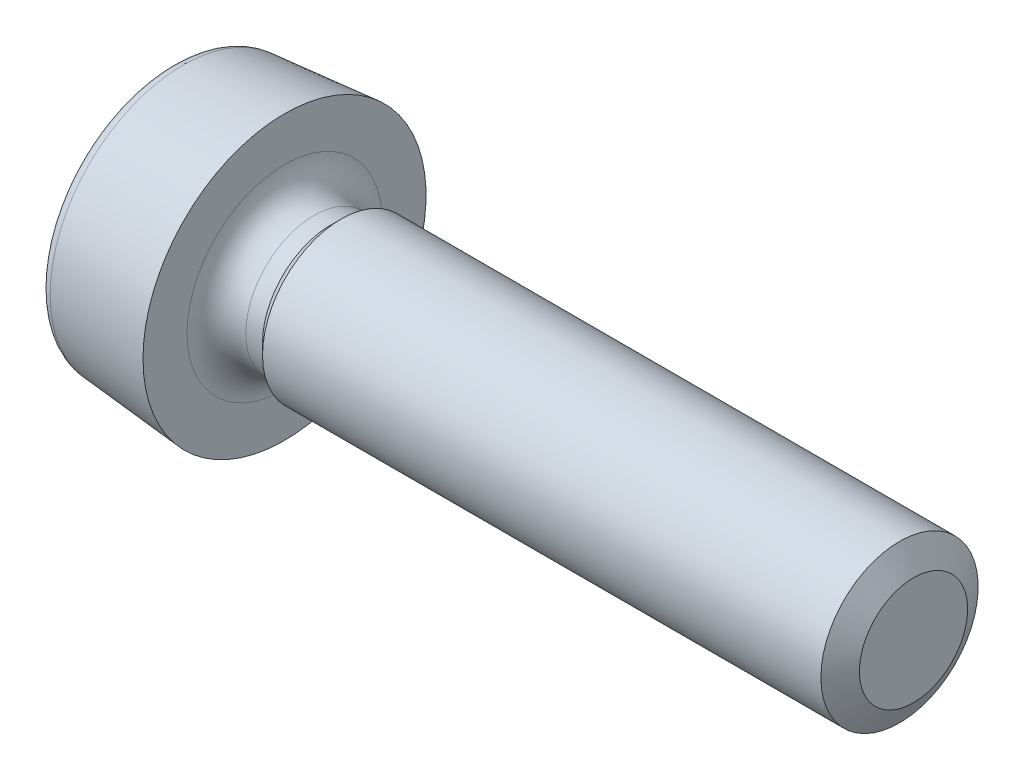
SolidWorks part; units mm, degrees
revolve "基体-旋转" add sketch "草图3" angle 360 about L0
sketch "草图3" plane through (0, 0, 0) normal (0, 0, 1) x (1, 0, 0)
  line L0 (-2.1696, 0) -> (16.014, 0) construction
  line L1 (0, 0) -> (11.8, 0)
  line L2 (11.8, 0) -> (11.8, 1.25)
  line L3 (11.8, 1.25) -> (2.7, 1.25)
  line L4 (2.7, 1.25) -> (2.5325, 1.0825)
  line L5 (2.5325, 1.0825) -> (2.2675, 1.0825)
  line L7 (1.8, 2.25) -> (0.1826, 2.1085)
  line L8 (0, 1.9093) -> (0, 0)
  line L9 (1.8, 1.55) -> (1.8, 2.25)
  arc A0 (1.8, 1.55) -> (2.2675, 1.0825) centre (2.2675, 1.55) ccw
  arc A1 (0.1826, 2.1085) -> (0, 1.9093) centre (0.2, 1.9093) ccw
  dimension "D4" = 0.2
  dimension "D1" = 5
  dimension "dk" = 4.5
  dimension "d" = 2.5
  dimension "D2" = 45
  dimension "da" = 3.1
  dimension "k" = 1.8
  dimension "D3" = 2.165
  dimension "a" = 0.9
  dimension "l" = 10
cosmetic thread "装饰螺纹线1" parameters "D2"=2.165
material "AISI 304"
ref_plane "前视" through (0, 0, 0) normal (0, 0, 1) x (1, 0, 0)
ref_plane "上视" through (0, 0, 0) normal (0, 1, 0) x (1, 0, 0)
ref_plane "右视" through (0, 0, 0) normal (1, 0, 0) x (0, 0, -1)
sketch "尺寸草图" plane through (0, 0, 0) normal (0, 0, 1) x (1, 0, 0)
  line L0 (0, 0) -> (10, 0)
  line L1 (0, 0) -> (0, 4.5)
  line L2 (10, 0) -> (10, 2.5)
  point P5 (0, 3.1)
  point P6 (1.8, 0)
  point P7 (2.7, 0)
  point P8 (9.55, 0)
  point P9 (8.8, 0)
  point P10 (7.3, 0)
  point P11 (0, 0.1)
  dimension "dk" = 4.5
  dimension "d" = 2.5
  dimension "da" = 3.1
  dimension "k" = 1.8
  dimension "a" = 0.9
  dimension "l" = 10
  dimension "P" = 0.45
  dimension "h" = 1.2
  dimension "m" = 2.7
  dimension "r" = 0.1
sketch "草图4" plane through (0, 0, 0) normal (0, 0, 1) x (1, 0, 0)
  line L0 (11.5774, 1.25) -> (12.0274, 1.25)
  line L1 (12.0274, 1.25) -> (11.8, 0.8603)
  line L2 (11.8, 0.8603) -> (11.5774, 1.25)
  line L3 (11.8, 1.25) -> (2.7, 1.25) construction
  line L4 (11.8, -1.25) -> (11.8, 1.25) construction
  line L5 (-0.218, 0) -> (14.7427, 0) construction
  line L6 (-2.1696, 0) -> (16.014, 0) construction
  dimension "D1" = 0.45
  dimension "D2" = 0.3897
  dimension "D3" = 60
revolve "切除-旋转1" cut sketch "草图4" angle 360 about L5
pattern_linear "阵列(线性)1" [suppressed] count 20 spacing 0.45 along (1, 0, 0)
sketch "草图5" plane through (0, 0, 0) normal (-1, 0, 0) x (0, 0, 1)
  line L1 (-0.225, 1.35) -> (0.225, 1.35)
  line L2 (-0.225, 1.35) -> (-0.225, -1.35)
  line L3 (-0.225, -1.35) -> (0.225, -1.35)
  line L4 (0.225, 1.35) -> (0.225, -1.35)
  point P4 (-0.225, 0)
  point P5 (0, 1.35)
  dimension "m" = 2.7
  dimension "D1" = 0.45
ref_plane "基准面1" through (1.2, 0, 0) normal (1, 0, 0) x (0, 0, -1)
sketch "草图6" plane through (1.2, 0, 0) normal (1, 0, 0) x (0, 0, -1)
  point P0 (0, 0)
loft "切除-放样1" cut profiles "草图5", "草图6"
pattern_circular "阵列(圆周)1" count 2 every 90 about axis through (0, 0, 0) along (1, 0, 0) of "切除-放样1"
equation "\"l@草图3\" = \"l@尺寸草图\""
equation "\"dk@草图3\" = \"dk@尺寸草图\""
equation "\"da@草图3\" = \"da@尺寸草图\""
equation "\"D4@草图3\" = \"r@尺寸草图\"*2"
equation "\"k@草图3\" = \"k@尺寸草图\""
equation "\"a@草图3\" = \"a@尺寸草图\""
equation "\"D3@草图3\" = \"d@尺寸草图\"*0.866"
equation "\"d@草图3\" = \"d@尺寸草图\""
equation "\"D2@装饰螺纹线1\" = \"d@尺寸草图\"*0.866"
equation "\"D1@草图4\" = \"P@尺寸草图\""
equation "\"D2@草图4\" = \"P@尺寸草图\"*0.866"
equation "\"D3@阵列(线性)1\" = \"P@尺寸草图\""
equation "\"D1@阵列(线性)1\" = (\"l@尺寸草图\"-\"a@尺寸草图\")/\"P@尺寸草图\""
equation "\"D1@基准面1\" = \"h@尺寸草图\""
equation "\"m@草图5\" = \"m@尺寸草图\""
equation "\"D1@草图5\" = \"P@尺寸草图\""
